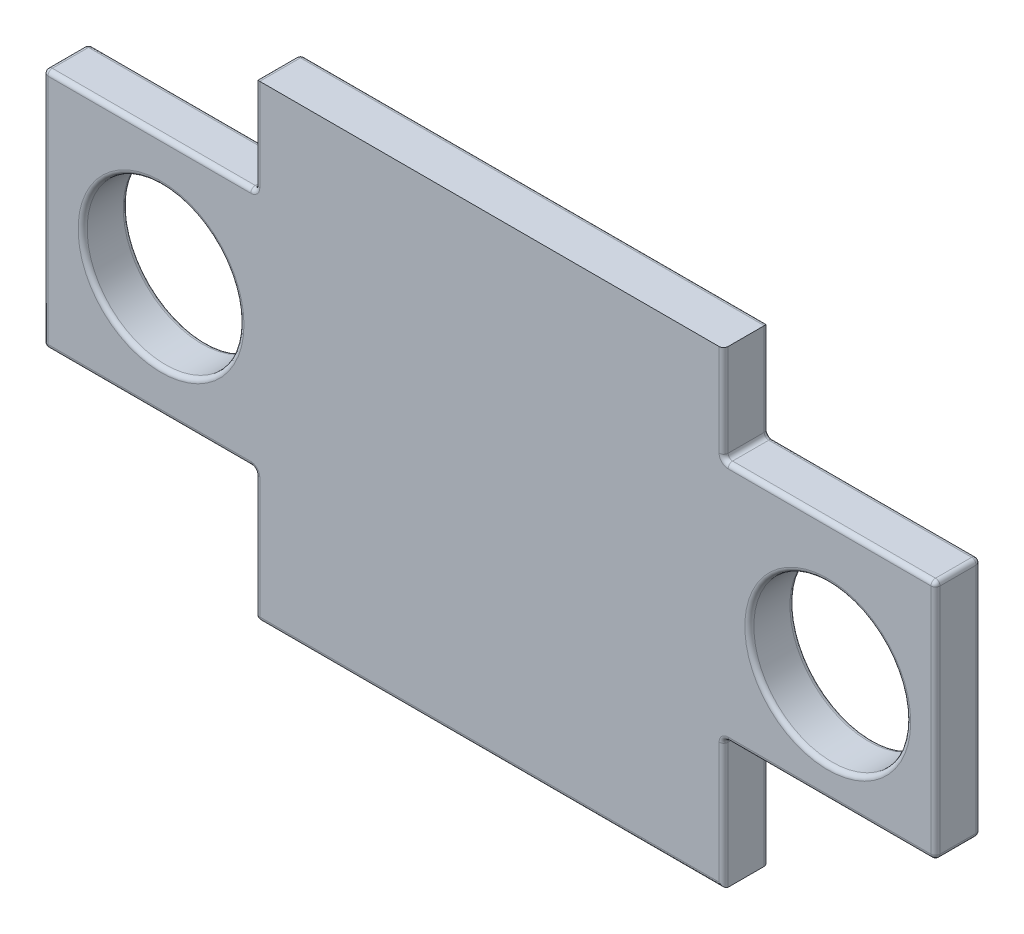
SolidWorks part; units mm, degrees
ref_plane "Front Plane" through (0, 0, 0) normal (0, 0, 1) x (1, 0, 0)
ref_plane "Top Plane" through (0, 0, 0) normal (0, 1, 0) x (1, 0, 0)
ref_plane "Right Plane" through (0, 0, 0) normal (1, 0, 0) x (0, 0, -1)
sketch "Sketch2" plane through (0, 0, 0) normal (0, 0, 1) x (1, 0, 0)
  line L1 (-10.375, 6.0805) -> (-19.5642, 6.0805)
  line L2 (-10.375, 6.0805) -> (-10.375, -4.6084)
  line L3 (-10.375, -4.6084) -> (-19.5642, -4.6084)
  line L4 (-19.7642, 5.8805) -> (-19.7642, -4.4084)
  line L6 (10.375, 6.0805) -> (19.5642, 6.0805)
  line L7 (10.375, 6.0805) -> (10.375, -4.6084)
  line L8 (10.375, -4.6084) -> (19.5642, -4.6084)
  line L9 (19.7642, 5.8805) -> (19.7642, -4.4084)
  circle A0 centre (-14.5492, 0.6881) radius 3.475
  circle A1 centre (14.9894, 0.208) radius 3.475
  arc A2 (-19.7642, -4.4084) -> (-19.5642, -4.6084) centre (-19.5642, -4.4084) ccw
  arc A3 (19.5642, -4.6084) -> (19.7642, -4.4084) centre (19.5642, -4.4084) ccw
  arc A4 (19.7642, 5.8805) -> (19.5642, 6.0805) centre (19.5642, 5.8805) ccw
  arc A5 (-19.5642, 6.0805) -> (-19.7642, 5.8805) centre (-19.5642, 5.8805) ccw
  dimension "D1" = 0.2
extrude "Boss-Extrude1" add sketch "Sketch2" along normal blind 2
sketch "Sketch3" plane through (0, 0, 2) normal (0, 0, 1) x (1, 0, 0)
  line L1 (-10.375, -10.375) -> (10.375, -10.375)
  line L2 (-10.375, -10.375) -> (-10.375, 10.375)
  line L3 (-10.375, 10.375) -> (10.375, 10.375)
  line L4 (10.375, -10.375) -> (10.375, 10.375)
  line L5 (-10.375, -10.375) -> (10.375, 10.375) construction
  line L6 (-10.375, 10.375) -> (10.375, -10.375) construction
  point P0 (0, 0)
  dimension "D1" = 20.75
extrude "Boss-Extrude2" add sketch "Sketch3" against normal blind 2
fillet "Fillet1" radius 0.2 41 edges at (-10.375, 6.0805, 1) (-10.375, -4.6084, 1) (-14.9696, -4.6084, 2) (-19.7056, -4.5498, 2) (-19.7642, 0.7361, 2) (-19.7056, 6.022, 2) (-14.9696, 6.0805, 2) (-14.9696, -4.6084, 0) (-19.7056, -4.5498, 0) (-19.7642, 0.7361, 0) (-19.7056, 6.022, 0) (-14.9696, 6.0805, 0) (-11.0742, 0.6881, 2) (-11.0742, 0.6881, 0) (-10.375, -10.375, 1) (-10.375, 10.375, 1) (0, -10.375, 2) (0, -10.375, 0) (-10.375, 8.2278, 2) (-10.375, 8.2278, 0) (-10.375, -7.4917, 2) (-10.375, -7.4917, 0) (0, 10.375, 0) (10.375, -7.4917, 2) (10.375, -7.4917, 0) (10.375, 8.2278, 2) (10.375, 8.2278, 0) (18.4644, 0.208, 0) (18.4644, 0.208, 2) (14.9696, -4.6084, 0) (19.7056, -4.5498, 0) (19.7642, 0.7361, 0) (19.7056, 6.022, 0) (14.9696, 6.0805, 0) (14.9696, -4.6084, 2) (19.7056, -4.5498, 2) (19.7642, 0.7361, 2) (19.7056, 6.022, 2) (14.9696, 6.0805, 2) (10.375, 6.0805, 1) (10.375, -4.6084, 1)
